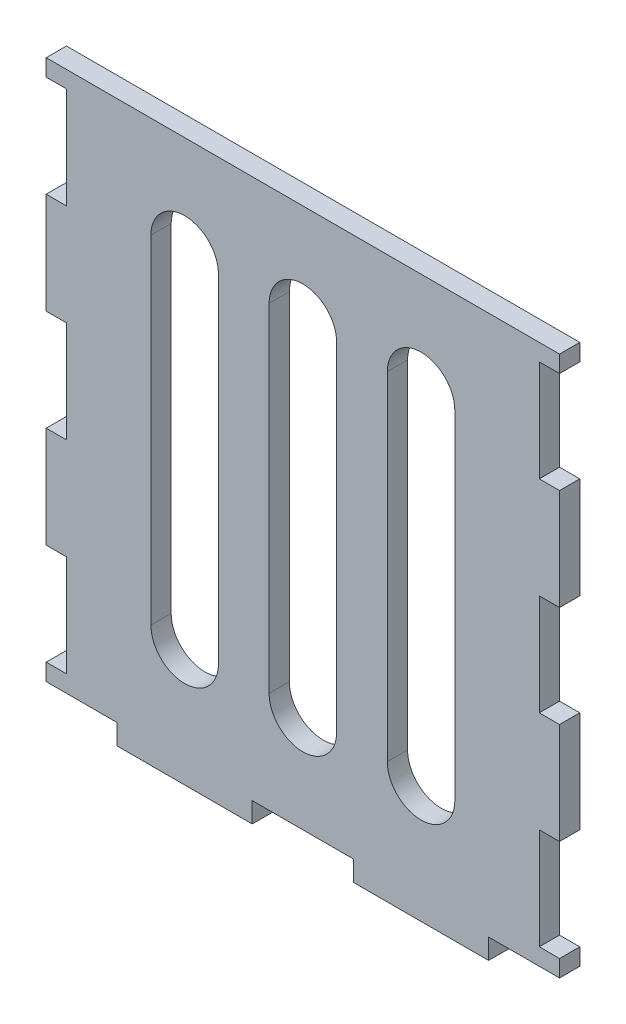
SolidWorks part; units mm, degrees
ref_plane "Front Plane" through (0, 0, 0) normal (0, 0, 1) x (1, 0, 0)
ref_plane "Top Plane" through (0, 0, 0) normal (0, 1, 0) x (1, 0, 0)
ref_plane "Right Plane" through (0, 0, 0) normal (1, 0, 0) x (0, 0, -1)
sketch "Sketch1" plane through (0, 0, 0) normal (0, 0, 1) x (1, 0, 0)
  line L0 (-35, 40) -> (35, 40)
  line L1 (38, -40) -> (-38, -40)
  line L2 (38, -40) -> (38, 40)
  line L3 (38, 40) -> (-38, 40)
  line L4 (-38, -40) -> (-38, 40)
  line L5 (38, -40) -> (-38, 40) construction
  line L6 (38, 40) -> (-38, -40) construction
  line L7 (-38, 40) -> (-35, 40)
  line L8 (35, 22.5) -> (38, 22.5)
  line L9 (35, 22.5) -> (35, 37.5)
  line L10 (35, 37.5) -> (38, 37.5)
  line L11 (38, 22.5) -> (38, 37.5)
  line L12 (35, 22.5) -> (38, 37.5) construction
  line L13 (35, 37.5) -> (38, 22.5) construction
  line L14 (35, -7.5) -> (38, -7.5)
  line L15 (35, -7.5) -> (35, 7.5)
  line L16 (35, 7.5) -> (38, 7.5)
  line L17 (38, -7.5) -> (38, 7.5)
  line L18 (35, -7.5) -> (38, 7.5) construction
  line L19 (35, 7.5) -> (38, -7.5) construction
  line L24 (0, -55) -> (0, 55) construction
  line L25 (-35, -22.5) -> (-38, -22.5)
  line L26 (27.5, -43) -> (7.5, -43)
  line L27 (27.5, -43) -> (27.5, -40)
  line L28 (27.5, -40) -> (7.5, -40)
  line L29 (7.5, -43) -> (7.5, -40)
  line L30 (27.5, -43) -> (7.5, -40) construction
  line L31 (27.5, -40) -> (7.5, -43) construction
  line L32 (-7.5, -43) -> (-27.5, -43)
  line L33 (-7.5, -43) -> (-7.5, -40)
  line L34 (-7.5, -40) -> (-27.5, -40)
  line L35 (-27.5, -43) -> (-27.5, -40)
  line L36 (-7.5, -43) -> (-27.5, -40) construction
  line L37 (-7.5, -40) -> (-27.5, -43) construction
  line L38 (35, -37.5) -> (38, -37.5)
  line L39 (35, -37.5) -> (35, -22.5)
  line L40 (35, -22.5) -> (38, -22.5)
  line L41 (38, -37.5) -> (38, -22.5)
  line L42 (35, -37.5) -> (38, -22.5) construction
  line L43 (35, -22.5) -> (38, -37.5) construction
  line L48 (-38, -37.5) -> (-38, -22.5)
  line L49 (-35, -37.5) -> (-38, -37.5)
  line L50 (-35, -37.5) -> (-35, -22.5)
  line L53 (17.5, -25) -> (17.5, 25) construction
  line L54 (12.5, -25) -> (12.5, 25)
  line L55 (22.5, -25) -> (22.5, 25)
  line L56 (-35, 7.5) -> (-38, 7.5)
  line L59 (-38, -7.5) -> (-38, 7.5)
  line L60 (-35, -7.5) -> (-38, -7.5)
  line L61 (-35, -7.5) -> (-35, 7.5)
  line L62 (-35, 37.5) -> (-38, 37.5)
  line L63 (-38, 22.5) -> (-38, 37.5)
  line L64 (-35, 22.5) -> (-38, 22.5)
  line L65 (-35, 22.5) -> (-35, 37.5)
  line L66 (0, -25) -> (0, 25) construction
  line L67 (-5, -25) -> (-5, 25)
  line L68 (5, -25) -> (5, 25)
  line L69 (-17.5, -25) -> (-17.5, 25) construction
  line L70 (-12.5, -25) -> (-12.5, 25)
  line L71 (-22.5, -25) -> (-22.5, 25)
  arc A2 (12.5, -25) -> (22.5, -25) centre (17.5, -25) ccw
  arc A3 (22.5, 25) -> (12.5, 25) centre (17.5, 25) ccw
  arc A6 (-5, -25) -> (5, -25) centre (0, -25) ccw
  arc A7 (5, 25) -> (-5, 25) centre (0, 25) ccw
  arc A8 (-12.5, -25) -> (-22.5, -25) centre (-17.5, -25) cw
  arc A9 (-22.5, 25) -> (-12.5, 25) centre (-17.5, 25) cw
  point P0 (0, 0)
  point P8 (36.5, 30)
  point P13 (36.5, 0)
  point P23 (17.5, -41.5)
  point P28 (-17.5, -41.5)
  point P34 (36.5, -30)
  point P50 (0, 0)
  point P51 (17.5, 0)
  point P62 (0, 0)
  point P63 (0, 0)
  point P66 (-17.5, 0)
  dimension "D18" = 5
  dimension "D1" = 76
  dimension "D2" = 80
  dimension "D3" = 3
  dimension "D4" = 80
  dimension "D5" = 3
  dimension "D6" = 15
  dimension "D7" = 15
  dimension "D8" = 15
  dimension "D12" = 3
  dimension "D13" = 20
  dimension "D14" = 15
  dimension "D15" = 7.5
  dimension "D20" = 50
extrude "Boss-Extrude1" add sketch "Sketch1" along normal blind 3
